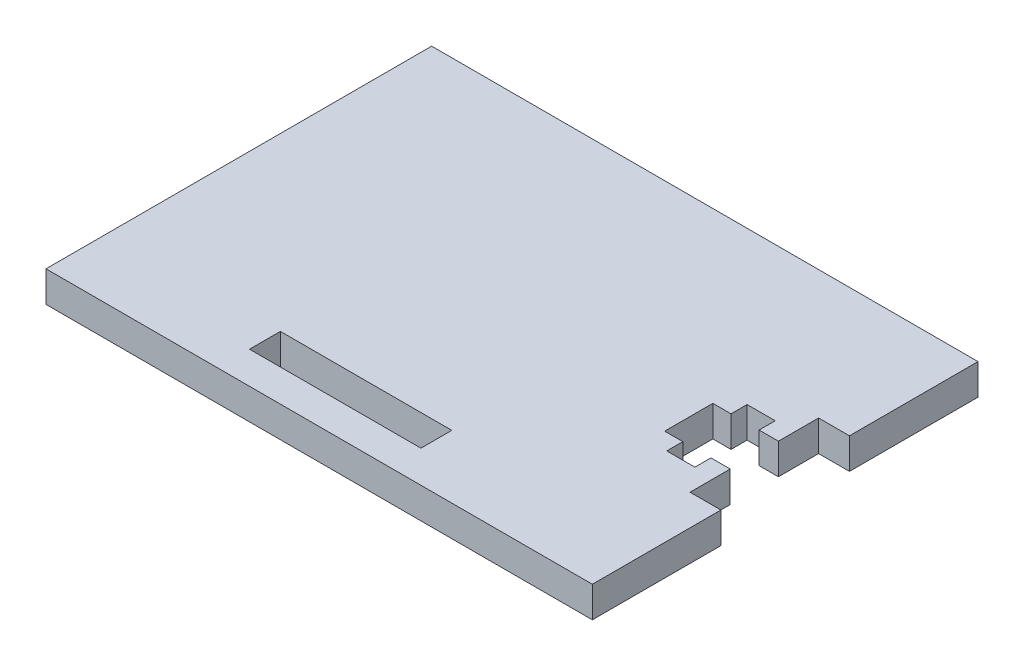
SolidWorks part; units mm, degrees
ref_plane "Front Plane" through (0, 0, 0) normal (0, 0, 1) x (1, 0, 0)
ref_plane "Top Plane" through (0, 0, 0) normal (0, 1, 0) x (1, 0, 0)
ref_plane "Right Plane" through (0, 0, 0) normal (1, 0, 0) x (0, 0, -1)
sketch "Sketch2" plane through (0, 0, 0) normal (0, 1, 0) x (1, 0, 0)
  line L0 (53.975, 25.4) -> (50.927, 25.4)
  line L1 (0, 0) -> (53.975, 0)
  line L2 (0, 0) -> (0, 38.1)
  line L3 (0, 38.1) -> (53.975, 38.1)
  line L4 (53.975, 0) -> (53.975, 12.7)
  line L5 (16.9333, 6.223) -> (33.8667, 6.223)
  line L6 (16.9333, 6.223) -> (16.9333, 3.175)
  line L7 (16.9333, 3.175) -> (33.8667, 3.175)
  line L8 (33.8667, 6.223) -> (33.8667, 3.175)
  line L9 (50.927, 25.4) -> (50.927, 21.4312)
  line L10 (50.927, 12.7) -> (53.975, 12.7)
  line L11 (50.927, 21.4312) -> (49.022, 21.4312)
  line L12 (49.022, 21.4312) -> (49.022, 23.0187)
  line L13 (49.022, 23.0187) -> (46.2439, 23.0187)
  line L14 (46.2439, 23.0187) -> (46.2439, 21.4312)
  line L15 (46.2439, 21.4312) -> (44.45, 21.4312)
  line L16 (44.45, 21.4312) -> (44.45, 16.6687)
  line L17 (44.45, 16.6687) -> (46.2439, 16.6687)
  line L18 (46.2439, 16.6687) -> (46.2439, 15.0812)
  line L19 (46.2439, 15.0812) -> (49.022, 15.0812)
  line L20 (49.022, 15.0812) -> (49.022, 16.6687)
  line L21 (49.022, 16.6687) -> (50.927, 16.6687)
  line L22 (50.927, 16.6687) -> (50.927, 12.7)
  line L23 (53.975, 25.4) -> (53.975, 38.1)
  dimension "D1" = 53.975
  dimension "D2" = 16.9333
  dimension "D3" = 3.048
  dimension "D4" = 3.175
  dimension "D5" = 16.9333
  dimension "D6" = 4.7625
  dimension "D7" = 3.048
  dimension "D8" = 2.7781
  dimension "D9" = 1.905
  dimension "D10" = 9.525
  dimension "D11" = 38.1
  dimension "D12" = 7.9375
  dimension "D13" = 12.7
extrude "Boss-Extrude1" add sketch "Sketch2" along normal blind 3.048 contours L0 L23 L3 L2 L1 L4 L10 L22 L21 L20 L19 L18 L17 L16 L15 L14 L13 L12 L11 L9 L5 L8 L7 L6
equation "\"Plywood thickness\"= 0.12in"
equation "\"D7@Sketch2\"=\"Plywood thickness\""
equation "\"D3@Sketch2\"=\"Plywood thickness\""
equation "\"D1@Boss-Extrude1\"=\"Plywood thickness\""
